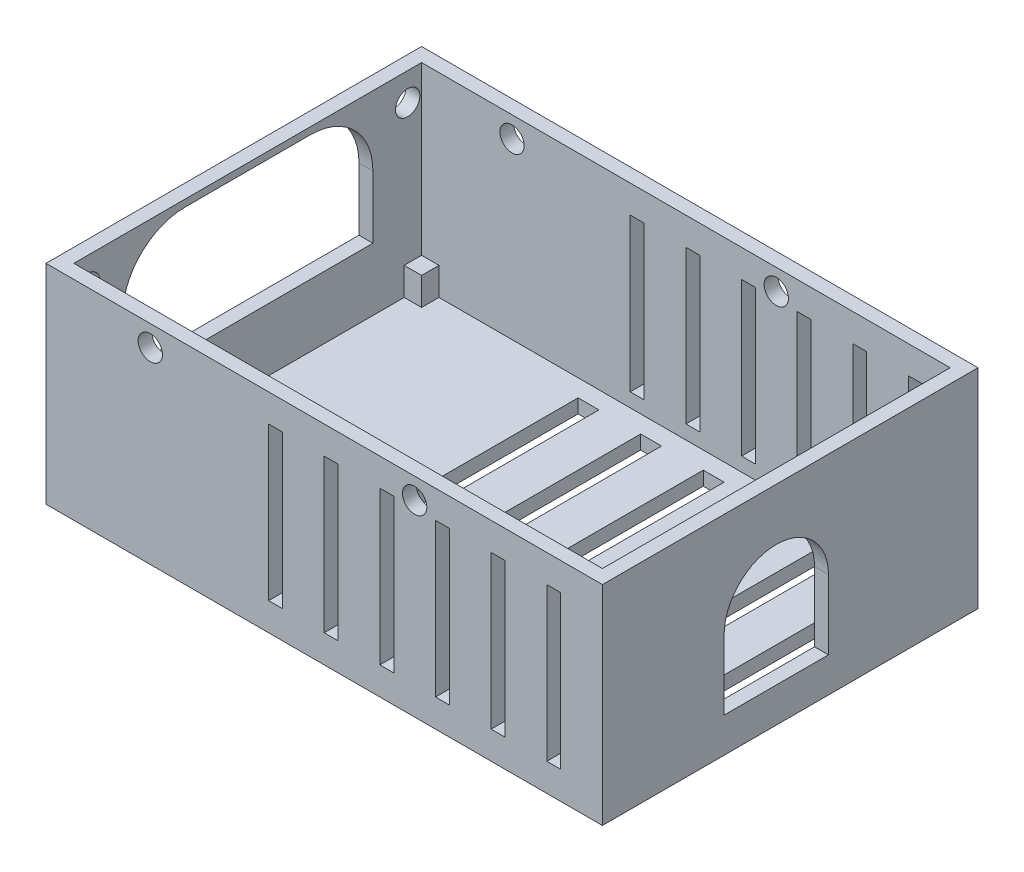
SolidWorks part; units mm, degrees
ref_plane "Front Plane" through (0, 0, 0) normal (0, 0, 1) x (1, 0, 0)
ref_plane "Top Plane" through (0, 0, 0) normal (0, 1, 0) x (1, 0, 0)
ref_plane "Right Plane" through (0, 0, 0) normal (1, 0, 0) x (0, 0, -1)
sketch "Sketch1" plane through (0, 0, 0) normal (0, 1, 0) x (1, 0, 0)
  line L1 (40, -27) -> (-40, -27)
  line L2 (40, -27) -> (40, 27)
  line L3 (40, 27) -> (-40, 27)
  line L4 (-40, -27) -> (-40, 27)
  line L5 (40, -27) -> (-40, 27) construction
  line L6 (40, 27) -> (-40, -27) construction
  point P0 (0, 0)
  dimension "D1" = 80
  dimension "D2" = 54
extrude "Boss-Extrude1" add sketch "Sketch1" along normal blind 30
sketch "Sketch2" plane through (0, 30, 0) normal (0, 1, 0) x (1, 0, 0)
  line L0 (40, 27) -> (-40, 27) construction
  line L1 (38, -25) -> (-38, -25)
  line L2 (38, -25) -> (38, 25)
  line L3 (38, 25) -> (-38, 25)
  line L4 (-38, -25) -> (-38, 25)
  line L5 (38, -25) -> (-38, 25) construction
  line L6 (38, 25) -> (-38, -25) construction
  line L7 (40, -27) -> (40, 27) construction
  point P0 (0, 0)
  dimension "D1" = 2
  dimension "D2" = 2
extrude "Cut-Extrude1" cut sketch "Sketch2" against normal blind 28
sketch "Sketch3" plane through (40, 0, 0) normal (1, 0, 0) x (0, 0, -1)
  line L2 (-27, 30) -> (-27, 0) construction
  line L3 (5.5, 15) -> (5.5, 5)
  line L4 (5.5, 5) -> (-9.5, 5)
  line L5 (-27, 0) -> (27, 0) construction
  line L6 (-9.5, 15) -> (-9.5, 5)
  line L8 (-2, 5) -> (-2, 31.1602) construction
  arc A0 (5.5, 15) -> (-9.5, 15) centre (-2, 15) ccw
  dimension "D3" = 7.5
  dimension "D1" = 15
  dimension "D2" = 10
  dimension "D4" = 25
  dimension "D5" = 5
extrude "Cut-Extrude2" cut sketch "Sketch3" against normal blind 6
sketch "Sketch4" plane through (-40, 0, 0) normal (-1, 0, 0) x (0, 0, 1)
  line L2 (0, 0) -> (0, 30) construction
  line L3 (-27, 0) -> (27, 0) construction
  line L4 (-27, 30) -> (27, 30) construction
  line L5 (0, 11) -> (0, 29) construction
  line L6 (-18, 29) -> (18, 29)
  line L7 (-18, 29) -> (-18, 11)
  line L8 (-18, 11) -> (18, 11)
  line L9 (18, 29) -> (18, 11)
  dimension "D1" = 18
  dimension "D3" = 11
  dimension "D2" = 36
extrude "Cut-Extrude3" cut sketch "Sketch4" against normal blind 6
sketch "Sketch5" plane through (0, 2, 0) normal (0, 1, 0) x (1, 0, 0)
  line L0 (0, 0) -> (-10, 0) construction
  line L1 (38, 25) -> (35.5, 25)
  line L2 (38, 25) -> (38, 22.5)
  line L3 (38, 22.5) -> (35.5, 22.5)
  line L4 (35.5, 25) -> (35.5, 22.5)
  line L5 (0, 0) -> (0, -10) construction
  line L6 (35.5, -25) -> (35.5, -22.5)
  line L7 (38, -22.5) -> (35.5, -22.5)
  line L8 (38, -25) -> (38, -22.5)
  line L9 (38, -25) -> (35.5, -25)
  line L10 (-38, -25) -> (-35.5, -25)
  line L11 (-38, -25) -> (-38, -22.5)
  line L12 (-38, -22.5) -> (-35.5, -22.5)
  line L13 (-35.5, -25) -> (-35.5, -22.5)
  line L14 (-35.5, 25) -> (-35.5, 22.5)
  line L15 (-38, 22.5) -> (-35.5, 22.5)
  line L16 (-38, 25) -> (-38, 22.5)
  line L17 (-38, 25) -> (-35.5, 25)
  dimension "D1" = 2.5
extrude "Standoffs" add sketch "Sketch5" along normal blind 4
fillet "Fillet3" radius 9 1 edges at (-39, 29, -18)
fillet "Fillet4" radius 9 1 edges at (-39, 29, 18)
sketch "Sketch6" plane through (0, 0, 0) normal (0, -1, 0) x (1, 0, 0)
  line L0 (40, 0) -> (37, 0) construction
  line L1 (32, -22.5) -> (35, -22.5)
  line L2 (32, -22.5) -> (32, 22.5)
  line L3 (32, 22.5) -> (35, 22.5)
  line L4 (35, -22.5) -> (35, 22.5)
  line L5 (32, -22.5) -> (35, 22.5) construction
  line L6 (32, 22.5) -> (35, -22.5) construction
  line L7 (29, -27) -> (29, 27) construction
  line L8 (40, -27) -> (-40, -27) construction
  line L9 (-40, 27) -> (40, 27) construction
  line L10 (26, -22.5) -> (23, -22.5)
  line L11 (26, 22.5) -> (23, -22.5) construction
  line L12 (26, -22.5) -> (23, 22.5) construction
  line L13 (23, -22.5) -> (23, 22.5)
  line L14 (26, 22.5) -> (23, 22.5)
  line L15 (26, -22.5) -> (26, 22.5)
  line L16 (20, -27) -> (20, 27) construction
  line L17 (14, -22.5) -> (17, 22.5) construction
  line L18 (14, 22.5) -> (17, -22.5) construction
  line L19 (8, 22.5) -> (5, -22.5) construction
  line L20 (8, -22.5) -> (5, 22.5) construction
  line L21 (0, 0) -> (3, 0) construction
  line L22 (14, -22.5) -> (14, 22.5)
  line L23 (14, 22.5) -> (17, 22.5)
  line L24 (17, -22.5) -> (17, 22.5)
  line L25 (40, 27) -> (40, -27) construction
  line L26 (14, -22.5) -> (17, -22.5)
  line L27 (5, -22.5) -> (5, 22.5)
  line L28 (8, 22.5) -> (5, 22.5)
  line L29 (8, -22.5) -> (8, 22.5)
  line L30 (8, -22.5) -> (5, -22.5)
  line L31 (2, -27) -> (2, 27) construction
  line L32 (4, 0) -> (1, 0) construction
  line L33 (-4, -22.5) -> (-1, 22.5) construction
  line L34 (-4, 22.5) -> (-1, -22.5) construction
  line L35 (-10, 22.5) -> (-13, -22.5) construction
  line L36 (-10, -22.5) -> (-13, 22.5) construction
  line L37 (-4, -22.5) -> (-1, -22.5)
  line L38 (-4, -22.5) -> (-4, 22.5)
  line L39 (-4, 22.5) -> (-1, 22.5)
  line L40 (-1, -22.5) -> (-1, 22.5)
  line L41 (-10, -22.5) -> (-13, -22.5)
  line L42 (-13, -22.5) -> (-13, 22.5)
  line L43 (-10, 22.5) -> (-13, 22.5)
  line L44 (-10, -22.5) -> (-10, 22.5)
  point P0 (33.5, 0)
  point P32 (6.5, 0)
  point P45 (-2.5, 0)
  dimension "D1" = 3
  dimension "D2" = 45
  dimension "D3" = 5
  dimension "D4" = 3
  dimension "D5" = 3
  dimension "D6" = 3
extrude "Bottom Grill" cut sketch "Sketch6" against normal up to surface (2 mm away) up to face at (0, 2, 0)
sketch "Sketch7" plane through (0, 0, -27) normal (0, 0, -1) x (-1, 0, 0)
  line L0 (-40, 30) -> (-40, 0) construction
  line L1 (-34, 4) -> (-32, 4)
  line L2 (-34, 4) -> (-34, 26)
  line L3 (-34, 26) -> (-32, 26)
  line L4 (-32, 4) -> (-32, 26)
  line L5 (-34, 4) -> (-32, 26) construction
  line L6 (-34, 26) -> (-32, 4) construction
  line L7 (-40, 15) -> (-37.7615, 15) construction
  line L8 (-29, 30) -> (-29, 0) construction
  line L9 (-40, 30) -> (40, 30) construction
  line L10 (-40, 0) -> (40, 0) construction
  line L11 (-24, 26) -> (-26, 26)
  line L12 (-26, 4) -> (-26, 26)
  line L13 (-24, 4) -> (-26, 4)
  line L14 (-24, 4) -> (-24, 26)
  line L15 (-21, 30) -> (-21, 0) construction
  line L16 (-2, 15) -> (-4.2385, 15) construction
  line L17 (-8, 26) -> (-10, 4) construction
  line L18 (-8, 4) -> (-10, 26) construction
  line L19 (-18, 4) -> (-18, 26)
  line L20 (-18, 4) -> (-16, 4)
  line L21 (-16, 4) -> (-16, 26)
  line L22 (-18, 26) -> (-16, 26)
  line L23 (-10, 4) -> (-10, 26)
  line L24 (-8, 26) -> (-10, 26)
  line L25 (-8, 4) -> (-8, 26)
  line L26 (-8, 4) -> (-10, 4)
  line L27 (-5, 30) -> (-5, 0) construction
  line L28 (-2, 4) -> (0, 26) construction
  line L29 (-2, 26) -> (0, 4) construction
  line L30 (-2, 4) -> (0, 4)
  line L31 (-2, 4) -> (-2, 26)
  line L32 (-2, 26) -> (0, 26)
  line L33 (0, 4) -> (0, 26)
  line L34 (8, 26) -> (6, 26)
  line L35 (6, 4) -> (6, 26)
  line L36 (8, 4) -> (6, 4)
  line L37 (8, 4) -> (8, 26)
  point P0 (-33, 15)
  point P31 (-9, 15)
  point P42 (-1, 15)
  dimension "D1" = 2
  dimension "D2" = 22
  dimension "D3" = 6
  dimension "D4" = 3
  dimension "D5" = 3
  dimension "D6" = 3
extrude "Cut-Extrude5" cut sketch "Sketch7" against normal up to surface (54 mm away) up to face at (0, 15, 27)
sketch "Sketch8" plane through (0, 0, -27) normal (0, 0, -1) x (-1, 0, 0)
  line L0 (-40, 30) -> (40, 30) construction
  line L1 (40, 30) -> (40, 0) construction
  circle A0 centre (-13, 27) radius 1.75
  circle A1 centre (25, 27) radius 1.75
  dimension "D1" = 3.5
  dimension "D4" = 15
  dimension "D2" = 3
  dimension "D3" = 3
extrude "Cut-Extrude6" cut sketch "Sketch8" against normal up to surface (54 mm away)
sketch "Sketch9" plane through (-40, 0, 0) normal (-1, 0, 0) x (0, 0, 1)
  line L0 (-27, 30) -> (-27, 0) construction
  line L1 (-27, 30) -> (27, 30) construction
  line L2 (0, 30) -> (0, 0) construction
  line L3 (-27, 0) -> (27, 0) construction
  circle A0 centre (-23, 26) radius 1.75
  circle A1 centre (23, 26) radius 1.75
  dimension "D1" = 3.5
  dimension "D2" = 4
  dimension "D3" = 4
extrude "Cut-Extrude7" cut sketch "Sketch9" against normal up to surface (2 mm away) up to face at (-38, 20.6213, 0)
